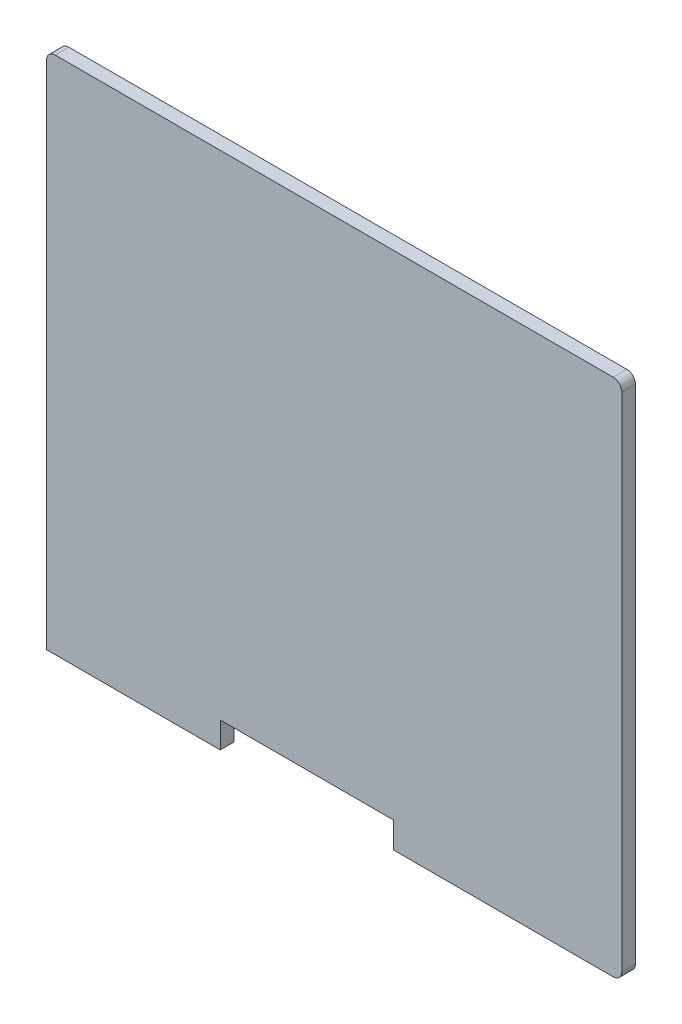
SolidWorks part; units mm, degrees
ref_plane "Front Plane" through (0, 0, 0) normal (0, 0, 1) x (1, 0, 0)
ref_plane "Top Plane" through (0, 0, 0) normal (0, 1, 0) x (1, 0, 0)
ref_plane "Right Plane" through (0, 0, 0) normal (1, 0, 0) x (0, 0, -1)
sketch "BPR2 PCB Outline" plane through (0, 0, 0) normal (0, 0, 1) x (1, 0, 0)
  line L0 (75.643, 7.3176) -> (75.643, 10.3176)
  line L1 (56.571, 67.3176) -> (121.041, 67.3176)
  line L2 (55.571, 66.3176) -> (55.571, 7.3176)
  line L3 (55.571, 7.3176) -> (75.643, 7.3176)
  line L4 (122.041, 66.3176) -> (122.041, 8.3176)
  line L5 (75.643, 10.3176) -> (95.643, 10.3176)
  line L6 (95.643, 10.3176) -> (95.643, 7.3176)
  line L7 (95.643, 7.3176) -> (121.041, 7.3176)
  arc A0 (121.041, 7.3176) -> (122.041, 8.3176) centre (121.041, 8.3176) ccw
  arc A1 (121.041, 67.3176) -> (122.041, 66.3176) centre (121.041, 66.3176) cw
  arc A2 (56.571, 67.3176) -> (55.571, 66.3176) centre (56.571, 66.3176) ccw
  point P6 (122.041, 7.3176)
  point P9 (122.041, 67.3176)
  point P12 (55.571, 67.3176)
  dimension "D4" = 25.398
  dimension "D3" = 1
  dimension "D1" = 60
  dimension "D5" = 20
  dimension "D6" = 3
sketch "23" plane through (0, 0, 0) normal (0, 0, 1) x (1, 0, 0)
  point P0 (0, 0)
extrude "Boss-Extrude1" add sketch "BPR2 PCB Outline" against normal blind 1.5748
